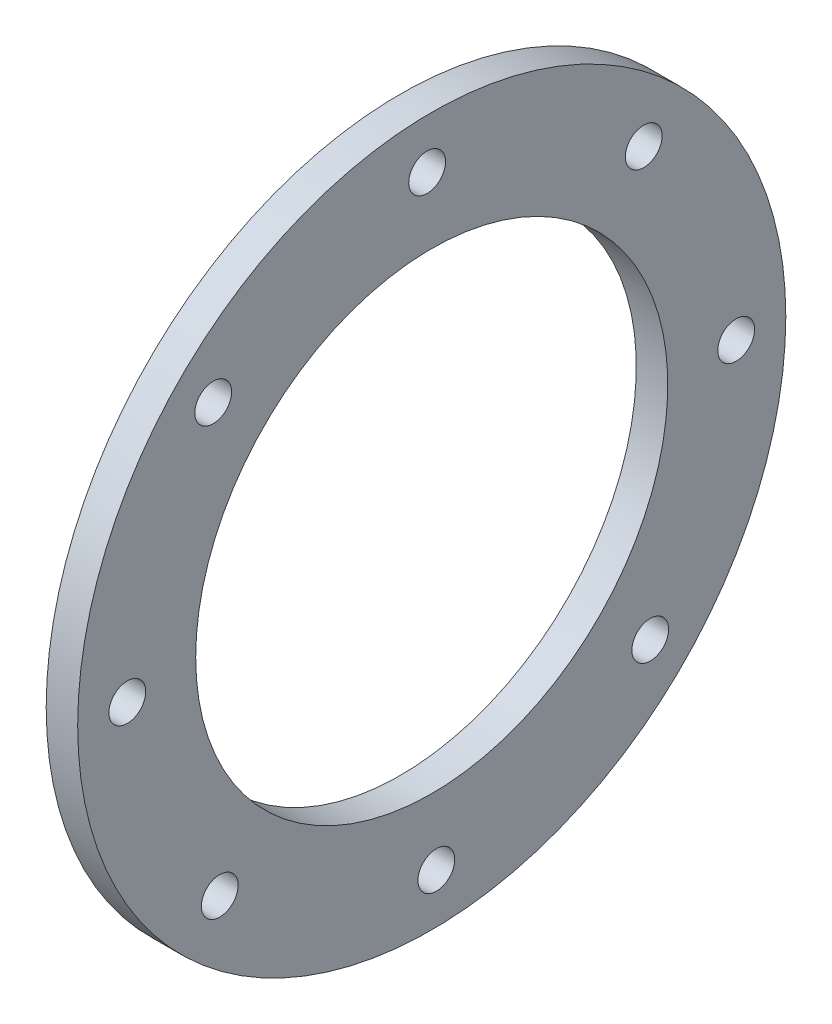
SolidWorks part; units mm, degrees
ref_plane "Front Plane" through (0, 0, 0) normal (0, 0, 1) x (1, 0, 0)
ref_plane "Top Plane" through (0, 0, 0) normal (0, 1, 0) x (1, 0, 0)
ref_plane "Right Plane" through (0, 0, 0) normal (1, 0, 0) x (0, 0, -1)
sketch "Sketch3" plane through (0, 0, 0) normal (0, 0, 1) x (1, 0, 0)
  line L0 (0, 0) -> (6.9333, 0) construction
  line L1 (-2, 30) -> (2, 30)
  line L2 (2, 30) -> (2, 45)
  line L3 (-2, 30) -> (-2, 45)
  line L4 (-2, 45) -> (2, 45)
  point P6 (0, 30)
  dimension "D1" = 4
  dimension "D2" = 15
  dimension "D3" = 30
revolve "Revolve1" add sketch "Sketch3" angle 360 about L0
sketch "Sketch4" plane through (-2, 0, 0) normal (-1, 0, 0) x (0, 0, 1)
  circle A0 centre (0.5858, 38.6898) radius 2.3396
  circle A1 centre (27.772, 26.9436) radius 2.3396
  circle A2 centre (38.6898, -0.5858) radius 2.3396
  circle A3 centre (26.9436, -27.772) radius 2.3396
  circle A4 centre (-0.5858, -38.6898) radius 2.3396
  circle A5 centre (-27.772, -26.9436) radius 2.3396
  circle A6 centre (-38.6898, 0.5858) radius 2.3396
  circle A7 centre (-26.9436, 27.772) radius 2.3396
  circle A8 centre (0, 0) radius 30 construction
  point P18 (0, 0)
  dimension "D1" = 8
extrude "Cut-Extrude1" cut sketch "Sketch4" against normal up to surface (4 mm away) up to face at (2, 0, 45)
